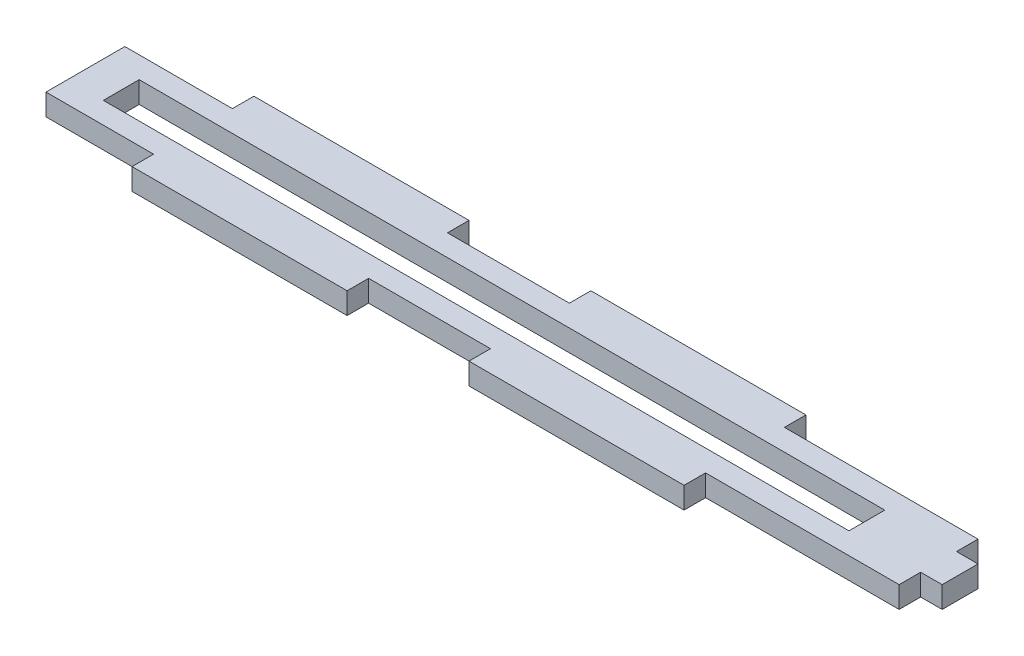
SolidWorks part; units mm, degrees
ref_plane "Plano frontal" through (0, 0, 0) normal (0, 0, 1) x (1, 0, 0)
ref_plane "Plano superior" through (0, 0, 0) normal (0, 1, 0) x (1, 0, 0)
ref_plane "Plano direito" through (0, 0, 0) normal (1, 0, 0) x (0, 0, -1)
sketch "Sketch1" plane through (0, 0, 0) normal (0, 1, 0) x (1, 0, 0)
  line L1 (-59.5, 5.5) -> (59.5, 5.5)
  line L2 (-59.5, 5.5) -> (-59.5, -5.5)
  line L3 (-59.5, -5.5) -> (59.5, -5.5)
  line L4 (59.5, 5.5) -> (59.5, -5.5)
  point P4 (0, 5.5)
  point P6 (-59.5, 0)
  dimension "D1" = 11
  dimension "D2" = 119
extrude "Boss-Extrude1" add sketch "Sketch1" along normal mid plane 3
sketch "Sketch2" plane through (0, 0, 0) normal (0, 1, 0) x (1, 0, 0)
  line L0 (-59.5, -5.5) -> (59.5, -5.5) construction
  line L1 (-44.5, -5.5) -> (-14.5, -5.5)
  line L2 (-44.5, -5.5) -> (-44.5, -8.5)
  line L3 (-44.5, -8.5) -> (-14.5, -8.5)
  line L4 (-14.5, -5.5) -> (-14.5, -8.5)
  line L11 (-1.65, 0) -> (1.65, 0) construction
  line L16 (-14.5, 5.5) -> (-14.5, 8.5)
  line L17 (-44.5, 8.5) -> (-14.5, 8.5)
  line L18 (-44.5, 5.5) -> (-44.5, 8.5)
  line L19 (-44.5, 5.5) -> (-14.5, 5.5)
  line L20 (-59.5, 5.5) -> (-59.5, -5.5) construction
  line L24 (32.5, -5.5) -> (2.5, -5.5)
  line L25 (32.5, -5.5) -> (32.5, -8.5)
  line L26 (32.5, -8.5) -> (2.5, -8.5)
  line L27 (2.5, -5.5) -> (2.5, -8.5)
  line L28 (2.5, 5.5) -> (2.5, 8.5)
  line L29 (32.5, 8.5) -> (2.5, 8.5)
  line L30 (32.5, 5.5) -> (32.5, 8.5)
  line L31 (32.5, 5.5) -> (2.5, 5.5)
  dimension "D1" = 15
  dimension "D2" = 3
  dimension "D3" = 30
  dimension "D4" = 17
extrude "Boss-Extrude2" add sketch "Sketch2" along normal mid plane 3
sketch "Sketch3" plane through (0, 0, 0) normal (0, 1, 0) x (1, 0, 0)
  line L0 (-59.5, 5.5) -> (-59.5, -5.5) construction
  line L7 (-54.5, 2.5) -> (49.5, 2.5)
  line L8 (-54.5, 2.5) -> (-54.5, -2.5)
  line L9 (-54.5, -2.5) -> (49.5, -2.5)
  line L10 (49.5, 2.5) -> (49.5, -2.5)
  line L11 (-44.5, 5.5) -> (-59.5, 5.5) construction
  point P8 (-54.5, 0)
  dimension "D3" = 5
  dimension "D1" = 5
  dimension "D2" = 3
  dimension "D4" = 104
extrude "Cut-Extrude1" cut sketch "Sketch3" against normal through all both and the other way through all
sketch "Sketch4" plane through (0, 0, 0) normal (0, 1, 0) x (1, 0, 0)
  line L0 (59.5, -5.5) -> (59.5, 5.5) construction
  line L1 (59.5, 2.5) -> (62.5, 2.5)
  line L2 (59.5, 2.5) -> (59.5, -2.5)
  line L3 (59.5, -2.5) -> (62.5, -2.5)
  line L4 (62.5, 2.5) -> (62.5, -2.5)
  line L5 (59.5, 5.5) -> (32.5, 5.5) construction
  point P6 (59.5, 0)
  dimension "D1" = 3
  dimension "D2" = 5
  dimension "D3" = 3
extrude "Boss-Extrude3" add sketch "Sketch4" along normal mid plane 3
